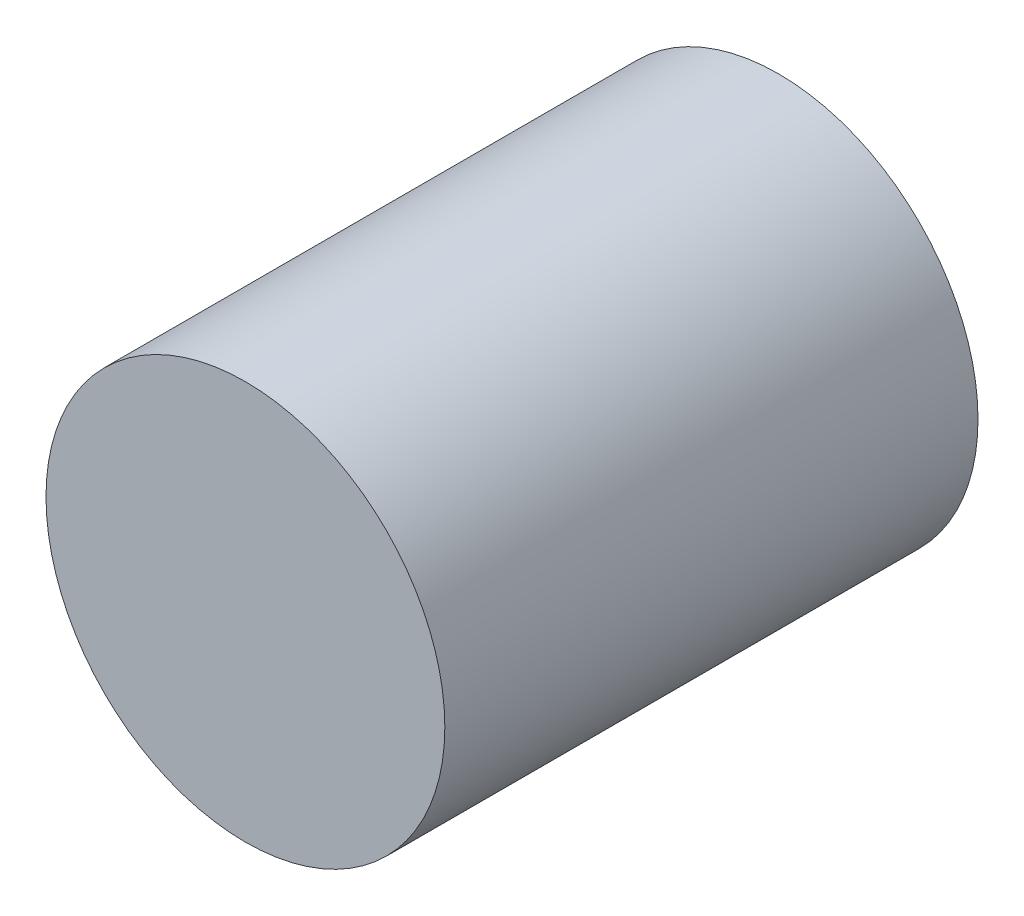
SolidWorks part; units mm, degrees
ref_plane "Front" through (0, 0, 0) normal (0, 0, 1) x (1, 0, 0)
ref_plane "Top" through (0, 0, 0) normal (0, 1, 0) x (1, 0, 0)
ref_plane "Right" through (0, 0, 0) normal (1, 0, 0) x (0, 0, -1)
sketch "Sketch1" plane through (0, 0, 0) normal (0, 0, 1) x (1, 0, 0)
  circle A0 centre (0, 0) radius 4.75
  dimension "D1" = 9.5
extrude "Base-Extrude" add sketch "Sketch1" along normal blind 12.7
